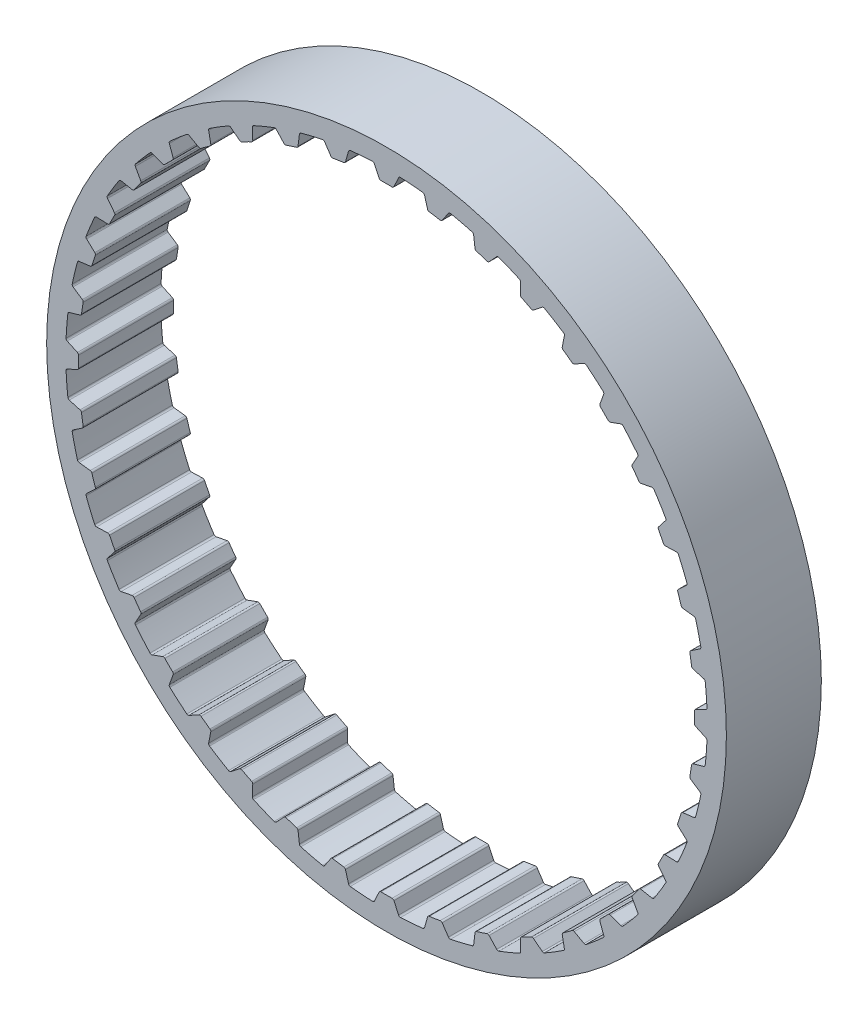
SolidWorks part; units mm, degrees
ref_plane "正面" through (0, 0, 0) normal (0, 0, 1) x (1, 0, 0)
ref_plane "平面" through (0, 0, 0) normal (0, 1, 0) x (1, 0, 0)
ref_plane "右側面" through (0, 0, 0) normal (1, 0, 0) x (0, 0, -1)
sketch "ｽｹｯﾁ1" plane through (0, 0, 0) normal (0, 0, 1) x (1, 0, 0)
  line L80 (31.3561, -6.1941) -> (30.4289, -5.5687)
  line L81 (30.6605, -4.1069) -> (31.7355, -3.7986)
  line L82 (31.939, -1.2127) -> (30.9254, -0.7401)
  line L83 (30.9254, 0.7401) -> (31.939, 1.2127)
  line L84 (31.7355, 3.7986) -> (30.6605, 4.1069)
  line L85 (30.4289, 5.5687) -> (31.3561, 6.1941)
  line L86 (30.7506, 8.7164) -> (29.6405, 8.8527)
  line L87 (29.1832, 10.2603) -> (30.0011, 11.0231)
  line L88 (29.0084, 13.4195) -> (27.8907, 13.3805)
  line L89 (27.2188, 14.6992) -> (27.9073, 15.5805)
  line L90 (26.552, 17.7922) -> (25.4542, 17.5788)
  line L91 (24.5842, 18.7762) -> (25.1264, 19.7544)
  line L92 (23.4418, 21.7268) -> (22.3909, 21.3443)
  line L93 (21.3443, 22.3909) -> (21.7268, 23.4418)
  line L94 (19.7544, 25.1264) -> (18.7762, 24.5842)
  line L95 (17.5788, 25.4542) -> (17.7922, 26.552)
  line L96 (15.5805, 27.9073) -> (14.6992, 27.2188)
  line L97 (13.3805, 27.8907) -> (13.4195, 29.0084)
  line L98 (11.0231, 30.0011) -> (10.2603, 29.1832)
  line L99 (8.8527, 29.6405) -> (8.7164, 30.7506)
  line L100 (6.1941, 31.3561) -> (5.5687, 30.4289)
  line L101 (4.1069, 30.6605) -> (3.7986, 31.7355)
  line L102 (1.2127, 31.939) -> (0.7401, 30.9254)
  line L103 (-0.7401, 30.9254) -> (-1.2127, 31.939)
  line L104 (-3.7986, 31.7355) -> (-4.1069, 30.6605)
  line L105 (-5.5687, 30.4289) -> (-6.1941, 31.3561)
  line L106 (-8.7164, 30.7506) -> (-8.8527, 29.6405)
  line L107 (-10.2603, 29.1832) -> (-11.0231, 30.0011)
  line L108 (-13.4195, 29.0084) -> (-13.3805, 27.8907)
  line L109 (-14.6992, 27.2188) -> (-15.5805, 27.9073)
  line L110 (-17.7922, 26.552) -> (-17.5788, 25.4542)
  line L111 (-18.7762, 24.5842) -> (-19.7544, 25.1264)
  line L112 (-21.7268, 23.4418) -> (-21.3443, 22.3909)
  line L113 (-22.3909, 21.3443) -> (-23.4418, 21.7268)
  line L114 (-25.1264, 19.7544) -> (-24.5842, 18.7762)
  line L115 (-25.4542, 17.5788) -> (-26.552, 17.7922)
  line L116 (-27.9073, 15.5805) -> (-27.2188, 14.6992)
  line L117 (-27.8907, 13.3805) -> (-29.0084, 13.4195)
  line L118 (-30.0011, 11.0231) -> (-29.1832, 10.2603)
  line L119 (-29.6405, 8.8527) -> (-30.7506, 8.7164)
  line L120 (-31.3561, 6.1941) -> (-30.4289, 5.5687)
  line L121 (-30.6605, 4.1069) -> (-31.7355, 3.7986)
  line L122 (-31.939, 1.2127) -> (-30.9254, 0.7401)
  line L123 (-30.9254, -0.7401) -> (-31.939, -1.2127)
  line L124 (-31.7355, -3.7986) -> (-30.6605, -4.1069)
  line L125 (-30.4289, -5.5687) -> (-31.3561, -6.1941)
  line L126 (-30.7506, -8.7164) -> (-29.6405, -8.8527)
  line L127 (-29.1832, -10.2603) -> (-30.0011, -11.0231)
  line L128 (-29.0084, -13.4195) -> (-27.8907, -13.3805)
  line L129 (-27.2188, -14.6992) -> (-27.9073, -15.5805)
  line L130 (-26.552, -17.7922) -> (-25.4542, -17.5788)
  line L131 (-24.5842, -18.7762) -> (-25.1264, -19.7544)
  line L132 (-23.4418, -21.7268) -> (-22.3909, -21.3443)
  line L133 (-21.3443, -22.3909) -> (-21.7268, -23.4418)
  line L134 (-19.7544, -25.1264) -> (-18.7762, -24.5842)
  line L135 (-17.5788, -25.4542) -> (-17.7922, -26.552)
  line L136 (-15.5805, -27.9073) -> (-14.6992, -27.2188)
  line L137 (-13.3805, -27.8907) -> (-13.4195, -29.0084)
  line L138 (-11.0231, -30.0011) -> (-10.2603, -29.1832)
  line L139 (-8.8527, -29.6405) -> (-8.7164, -30.7506)
  line L140 (-6.1941, -31.3561) -> (-5.5687, -30.4289)
  line L141 (-4.1069, -30.6605) -> (-3.7986, -31.7355)
  line L142 (-1.2127, -31.939) -> (-0.7401, -30.9254)
  line L143 (0.7401, -30.9254) -> (1.2127, -31.939)
  line L144 (3.7986, -31.7355) -> (4.1069, -30.6605)
  line L145 (5.5687, -30.4289) -> (6.1941, -31.3561)
  line L146 (8.7164, -30.7506) -> (8.8527, -29.6405)
  line L147 (10.2603, -29.1832) -> (11.0231, -30.0011)
  line L148 (13.4195, -29.0084) -> (13.3805, -27.8907)
  line L149 (14.6992, -27.2188) -> (15.5805, -27.9073)
  line L150 (17.7922, -26.552) -> (17.5788, -25.4542)
  line L151 (18.7762, -24.5842) -> (19.7544, -25.1264)
  line L152 (21.7268, -23.4418) -> (21.3443, -22.3909)
  line L153 (22.3909, -21.3443) -> (23.4418, -21.7268)
  line L154 (25.1264, -19.7544) -> (24.5842, -18.7762)
  line L155 (25.4542, -17.5788) -> (26.552, -17.7922)
  line L156 (27.9073, -15.5805) -> (27.2188, -14.6992)
  line L157 (27.8907, -13.3805) -> (29.0084, -13.4195)
  line L158 (30.0011, -11.0231) -> (29.1832, -10.2603)
  line L159 (29.6405, -8.8527) -> (30.7506, -8.7164)
  line L160 (31.3561, -6.1941) -> (30.4289, -5.5687)
  line L161 (30.6605, -4.1069) -> (31.7355, -3.7986)
  line L162 (31.939, -1.2127) -> (30.9254, -0.7401)
  line L163 (30.9254, 0.7401) -> (31.939, 1.2127)
  line L164 (31.7355, 3.7986) -> (30.6605, 4.1069)
  line L165 (30.4289, 5.5687) -> (31.3561, 6.1941)
  line L166 (30.7506, 8.7164) -> (29.6405, 8.8527)
  line L167 (29.1832, 10.2603) -> (30.0011, 11.0231)
  line L168 (29.0084, 13.4195) -> (27.8907, 13.3805)
  line L169 (27.2188, 14.6992) -> (27.9073, 15.5805)
  line L170 (26.552, 17.7922) -> (25.4542, 17.5788)
  line L171 (24.5842, 18.7762) -> (25.1264, 19.7544)
  line L172 (23.4418, 21.7268) -> (22.3909, 21.3443)
  line L173 (21.3443, 22.3909) -> (21.7268, 23.4418)
  line L174 (19.7544, 25.1264) -> (18.7762, 24.5842)
  line L175 (17.5788, 25.4542) -> (17.7922, 26.552)
  line L176 (15.5805, 27.9073) -> (14.6992, 27.2188)
  line L177 (13.3805, 27.8907) -> (13.4195, 29.0084)
  line L178 (11.0231, 30.0011) -> (10.2603, 29.1832)
  line L179 (8.8527, 29.6405) -> (8.7164, 30.7506)
  line L180 (6.1941, 31.3561) -> (5.5687, 30.4289)
  line L181 (4.1069, 30.6605) -> (3.7986, 31.7355)
  line L182 (1.2127, 31.939) -> (0.7401, 30.9254)
  line L183 (-0.7401, 30.9254) -> (-1.2127, 31.939)
  line L184 (-3.7986, 31.7355) -> (-4.1069, 30.6605)
  line L185 (-5.5687, 30.4289) -> (-6.1941, 31.3561)
  line L186 (-8.7164, 30.7506) -> (-8.8527, 29.6405)
  line L187 (-10.2603, 29.1832) -> (-11.0231, 30.0011)
  line L188 (-13.4195, 29.0084) -> (-13.3805, 27.8907)
  line L189 (-14.6992, 27.2188) -> (-15.5805, 27.9073)
  line L190 (-17.7922, 26.552) -> (-17.5788, 25.4542)
  line L191 (-18.7762, 24.5842) -> (-19.7544, 25.1264)
  line L192 (-21.7268, 23.4418) -> (-21.3443, 22.3909)
  line L193 (-22.3909, 21.3443) -> (-23.4418, 21.7268)
  line L194 (-25.1264, 19.7544) -> (-24.5842, 18.7762)
  line L195 (-25.4542, 17.5788) -> (-26.552, 17.7922)
  line L196 (-27.9073, 15.5805) -> (-27.2188, 14.6992)
  line L197 (-27.8907, 13.3805) -> (-29.0084, 13.4195)
  line L198 (-30.0011, 11.0231) -> (-29.1832, 10.2603)
  line L199 (-29.6405, 8.8527) -> (-30.7506, 8.7164)
  line L200 (-31.3561, 6.1941) -> (-30.4289, 5.5687)
  line L201 (-30.6605, 4.1069) -> (-31.7355, 3.7986)
  line L202 (-31.939, 1.2127) -> (-30.9254, 0.7401)
  line L203 (-30.9254, -0.7401) -> (-31.939, -1.2127)
  line L204 (-31.7355, -3.7986) -> (-30.6605, -4.1069)
  line L205 (-30.4289, -5.5687) -> (-31.3561, -6.1941)
  line L206 (-30.7506, -8.7164) -> (-29.6405, -8.8527)
  line L207 (-29.1832, -10.2603) -> (-30.0011, -11.0231)
  line L208 (-29.0084, -13.4195) -> (-27.8907, -13.3805)
  line L209 (-27.2188, -14.6992) -> (-27.9073, -15.5805)
  line L210 (-26.552, -17.7922) -> (-25.4542, -17.5788)
  line L211 (-24.5842, -18.7762) -> (-25.1264, -19.7544)
  line L212 (-23.4418, -21.7268) -> (-22.3909, -21.3443)
  line L213 (-21.3443, -22.3909) -> (-21.7268, -23.4418)
  line L214 (-19.7544, -25.1264) -> (-18.7762, -24.5842)
  line L215 (-17.5788, -25.4542) -> (-17.7922, -26.552)
  line L216 (-15.5805, -27.9073) -> (-14.6992, -27.2188)
  line L217 (-13.3805, -27.8907) -> (-13.4195, -29.0084)
  line L218 (-11.0231, -30.0011) -> (-10.2603, -29.1832)
  line L219 (-8.8527, -29.6405) -> (-8.7164, -30.7506)
  line L220 (-6.1941, -31.3561) -> (-5.5687, -30.4289)
  line L221 (-4.1069, -30.6605) -> (-3.7986, -31.7355)
  line L222 (-1.2127, -31.939) -> (-0.7401, -30.9254)
  line L223 (0.7401, -30.9254) -> (1.2127, -31.939)
  line L224 (3.7986, -31.7355) -> (4.1069, -30.6605)
  line L225 (5.5687, -30.4289) -> (6.1941, -31.3561)
  line L226 (8.7164, -30.7506) -> (8.8527, -29.6405)
  line L227 (10.2603, -29.1832) -> (11.0231, -30.0011)
  line L228 (13.4195, -29.0084) -> (13.3805, -27.8907)
  line L229 (14.6992, -27.2188) -> (15.5805, -27.9073)
  line L230 (17.7922, -26.552) -> (17.5788, -25.4542)
  line L231 (18.7762, -24.5842) -> (19.7544, -25.1264)
  line L232 (21.7268, -23.4418) -> (21.3443, -22.3909)
  line L233 (22.3909, -21.3443) -> (23.4418, -21.7268)
  line L234 (25.1264, -19.7544) -> (24.5842, -18.7762)
  line L235 (25.4542, -17.5788) -> (26.552, -17.7922)
  line L236 (27.9073, -15.5805) -> (27.2188, -14.6992)
  line L237 (27.8907, -13.3805) -> (29.0084, -13.4195)
  line L238 (30.0011, -11.0231) -> (29.1832, -10.2603)
  line L239 (29.6405, -8.8527) -> (30.7506, -8.7164)
  circle A0 centre (0, 0) radius 34
  arc A240 (30.7506, -8.7164) -> (30.9189, -8.5713) centre (30.7262, -8.5179) ccw
  arc A241 (30.9189, -8.5713) -> (31.4403, -6.3998) centre (0, 0) ccw
  arc A242 (31.4403, -6.3998) -> (31.3561, -6.1941) centre (31.2443, -6.3599) ccw
  arc A243 (30.3438, -5.3681) -> (30.4289, -5.5687) centre (30.5408, -5.4029) ccw
  arc A244 (30.3438, -5.3681) -> (30.5175, -4.2714) centre (0, 0) ccw
  arc A245 (30.6605, -4.1069) -> (30.5175, -4.2714) centre (30.7156, -4.2991) ccw
  arc A246 (31.7355, -3.7986) -> (31.8791, -3.629) centre (31.6804, -3.6063) ccw
  arc A247 (31.8791, -3.629) -> (32.0543, -1.4027) centre (0, 0) ccw
  arc A248 (32.0543, -1.4027) -> (31.939, -1.2127) centre (31.8545, -1.394) ccw
  arc A249 (30.81, -0.5552) -> (30.9254, -0.7401) centre (31.01, -0.5588) ccw
  arc A250 (30.81, -0.5552) -> (30.81, 0.5552) centre (0, 0) ccw
  arc A251 (30.9254, 0.7401) -> (30.81, 0.5552) centre (31.01, 0.5588) ccw
  arc A252 (31.939, 1.2127) -> (32.0543, 1.4027) centre (31.8545, 1.394) ccw
  arc A253 (32.0543, 1.4027) -> (31.8791, 3.629) centre (0, 0) ccw
  arc A254 (31.8791, 3.629) -> (31.7355, 3.7986) centre (31.6804, 3.6063) ccw
  arc A255 (30.5175, 4.2714) -> (30.6605, 4.1069) centre (30.7156, 4.2991) ccw
  arc A256 (30.5175, 4.2714) -> (30.3438, 5.3681) centre (0, 0) ccw
  arc A257 (30.4289, 5.5687) -> (30.3438, 5.3681) centre (30.5408, 5.4029) ccw
  arc A258 (31.3561, 6.1941) -> (31.4403, 6.3998) centre (31.2443, 6.3599) ccw
  arc A259 (31.4403, 6.3998) -> (30.9189, 8.5713) centre (0, 0) ccw
  arc A260 (30.9189, 8.5713) -> (30.7506, 8.7164) centre (30.7262, 8.5179) ccw
  arc A261 (29.4736, 8.9928) -> (29.6405, 8.8527) centre (29.6649, 9.0512) ccw
  arc A262 (29.4736, 8.9928) -> (29.1305, 10.0488) centre (0, 0) ccw
  arc A263 (29.1832, 10.2603) -> (29.1305, 10.0488) centre (29.3196, 10.114) ccw
  arc A264 (30.0011, 11.0231) -> (30.052, 11.2394) centre (29.8647, 11.1693) ccw
  arc A265 (30.052, 11.2394) -> (29.1974, 13.3025) centre (0, 0) ccw
  arc A266 (29.1974, 13.3025) -> (29.0084, 13.4195) centre (29.0154, 13.2196) ccw
  arc A267 (27.704, 13.4928) -> (27.8907, 13.3805) centre (27.8838, 13.5803) ccw
  arc A268 (27.704, 13.4928) -> (27.1999, 14.4821) centre (0, 0) ccw
  arc A269 (27.2188, 14.6992) -> (27.1999, 14.4821) centre (27.3764, 14.5761) ccw
  arc A270 (27.9073, 15.5805) -> (27.9238, 15.8022) centre (27.7497, 15.7037) ccw
  arc A271 (27.9238, 15.8022) -> (26.757, 17.7062) centre (0, 0) ccw
  arc A272 (26.757, 17.7062) -> (26.552, 17.7922) centre (26.5902, 17.5959) ccw
  arc A273 (25.2521, 17.6605) -> (25.4542, 17.5788) centre (25.416, 17.7751) ccw
  arc A274 (25.2521, 17.6605) -> (24.5995, 18.5588) centre (0, 0) ccw
  arc A275 (24.5842, 18.7762) -> (24.5995, 18.5588) centre (24.7591, 18.6793) ccw
  arc A276 (25.1264, 19.7544) -> (25.108, 19.9759) centre (24.9515, 19.8514) ccw
  arc A277 (25.108, 19.9759) -> (23.6577, 21.674) centre (0, 0) ccw
  arc A278 (23.6577, 21.674) -> (23.4418, 21.7268) centre (23.5102, 21.5389) ccw
  arc A279 (22.1785, 21.3934) -> (22.3909, 21.3443) centre (22.3225, 21.5322) ccw
  arc A280 (22.1785, 21.3934) -> (21.3934, 22.1785) centre (0, 0) ccw
  arc A281 (21.3443, 22.3909) -> (21.3934, 22.1785) centre (21.5322, 22.3225) ccw
  arc A282 (21.7268, 23.4418) -> (21.674, 23.6577) centre (21.5389, 23.5102) ccw
  arc A283 (21.674, 23.6577) -> (19.9759, 25.108) centre (0, 0) ccw
  arc A284 (19.9759, 25.108) -> (19.7544, 25.1264) centre (19.8514, 24.9515) ccw
  arc A285 (18.5588, 24.5995) -> (18.7762, 24.5842) centre (18.6793, 24.7591) ccw
  arc A286 (18.5588, 24.5995) -> (17.6605, 25.2521) centre (0, 0) ccw
  arc A287 (17.5788, 25.4542) -> (17.6605, 25.2521) centre (17.7751, 25.416) ccw
  arc A288 (17.7922, 26.552) -> (17.7062, 26.757) centre (17.5959, 26.5902) ccw
  arc A289 (17.7062, 26.757) -> (15.8022, 27.9238) centre (0, 0) ccw
  arc A290 (15.8022, 27.9238) -> (15.5805, 27.9073) centre (15.7037, 27.7497) ccw
  arc A291 (14.4821, 27.1999) -> (14.6992, 27.2188) centre (14.5761, 27.3764) ccw
  arc A292 (14.4821, 27.1999) -> (13.4928, 27.704) centre (0, 0) ccw
  arc A293 (13.3805, 27.8907) -> (13.4928, 27.704) centre (13.5803, 27.8838) ccw
  arc A294 (13.4195, 29.0084) -> (13.3025, 29.1974) centre (13.2196, 29.0154) ccw
  arc A295 (13.3025, 29.1974) -> (11.2394, 30.052) centre (0, 0) ccw
  arc A296 (11.2394, 30.052) -> (11.0231, 30.0011) centre (11.1693, 29.8647) ccw
  arc A297 (10.0488, 29.1305) -> (10.2603, 29.1832) centre (10.114, 29.3196) ccw
  arc A298 (10.0488, 29.1305) -> (8.9928, 29.4736) centre (0, 0) ccw
  arc A299 (8.8527, 29.6405) -> (8.9928, 29.4736) centre (9.0512, 29.6649) ccw
  arc A300 (8.7164, 30.7506) -> (8.5713, 30.9189) centre (8.5179, 30.7262) ccw
  arc A301 (8.5713, 30.9189) -> (6.3998, 31.4403) centre (0, 0) ccw
  arc A302 (6.3998, 31.4403) -> (6.1941, 31.3561) centre (6.3599, 31.2443) ccw
  arc A303 (5.3681, 30.3438) -> (5.5687, 30.4289) centre (5.4029, 30.5408) ccw
  arc A304 (5.3681, 30.3438) -> (4.2714, 30.5175) centre (0, 0) ccw
  arc A305 (4.1069, 30.6605) -> (4.2714, 30.5175) centre (4.2991, 30.7156) ccw
  arc A306 (3.7986, 31.7355) -> (3.629, 31.8791) centre (3.6063, 31.6804) ccw
  arc A307 (3.629, 31.8791) -> (1.4027, 32.0543) centre (0, 0) ccw
  arc A308 (1.4027, 32.0543) -> (1.2127, 31.939) centre (1.394, 31.8545) ccw
  arc A309 (0.5552, 30.81) -> (0.7401, 30.9254) centre (0.5588, 31.01) ccw
  arc A310 (0.5552, 30.81) -> (-0.5552, 30.81) centre (0, 0) ccw
  arc A311 (-0.7401, 30.9254) -> (-0.5552, 30.81) centre (-0.5588, 31.01) ccw
  arc A312 (-1.2127, 31.939) -> (-1.4027, 32.0543) centre (-1.394, 31.8545) ccw
  arc A313 (-1.4027, 32.0543) -> (-3.629, 31.8791) centre (0, 0) ccw
  arc A314 (-3.629, 31.8791) -> (-3.7986, 31.7355) centre (-3.6063, 31.6804) ccw
  arc A315 (-4.2714, 30.5175) -> (-4.1069, 30.6605) centre (-4.2991, 30.7156) ccw
  arc A316 (-4.2714, 30.5175) -> (-5.3681, 30.3438) centre (0, 0) ccw
  arc A317 (-5.5687, 30.4289) -> (-5.3681, 30.3438) centre (-5.4029, 30.5408) ccw
  arc A318 (-6.1941, 31.3561) -> (-6.3998, 31.4403) centre (-6.3599, 31.2443) ccw
  arc A319 (-6.3998, 31.4403) -> (-8.5713, 30.9189) centre (0, 0) ccw
  arc A320 (-8.5713, 30.9189) -> (-8.7164, 30.7506) centre (-8.5179, 30.7262) ccw
  arc A321 (-8.9928, 29.4736) -> (-8.8527, 29.6405) centre (-9.0512, 29.6649) ccw
  arc A322 (-8.9928, 29.4736) -> (-10.0488, 29.1305) centre (0, 0) ccw
  arc A323 (-10.2603, 29.1832) -> (-10.0488, 29.1305) centre (-10.114, 29.3196) ccw
  arc A324 (-11.0231, 30.0011) -> (-11.2394, 30.052) centre (-11.1693, 29.8647) ccw
  arc A325 (-11.2394, 30.052) -> (-13.3025, 29.1974) centre (0, 0) ccw
  arc A326 (-13.3025, 29.1974) -> (-13.4195, 29.0084) centre (-13.2196, 29.0154) ccw
  arc A327 (-13.4928, 27.704) -> (-13.3805, 27.8907) centre (-13.5803, 27.8838) ccw
  arc A328 (-13.4928, 27.704) -> (-14.4821, 27.1999) centre (0, 0) ccw
  arc A329 (-14.6992, 27.2188) -> (-14.4821, 27.1999) centre (-14.5761, 27.3764) ccw
  arc A330 (-15.5805, 27.9073) -> (-15.8022, 27.9238) centre (-15.7037, 27.7497) ccw
  arc A331 (-15.8022, 27.9238) -> (-17.7062, 26.757) centre (0, 0) ccw
  arc A332 (-17.7062, 26.757) -> (-17.7922, 26.552) centre (-17.5959, 26.5902) ccw
  arc A333 (-17.6605, 25.2521) -> (-17.5788, 25.4542) centre (-17.7751, 25.416) ccw
  arc A334 (-17.6605, 25.2521) -> (-18.5588, 24.5995) centre (0, 0) ccw
  arc A335 (-18.7762, 24.5842) -> (-18.5588, 24.5995) centre (-18.6793, 24.7591) ccw
  arc A336 (-19.7544, 25.1264) -> (-19.9759, 25.108) centre (-19.8514, 24.9515) ccw
  arc A337 (-19.9759, 25.108) -> (-21.674, 23.6577) centre (0, 0) ccw
  arc A338 (-21.674, 23.6577) -> (-21.7268, 23.4418) centre (-21.5389, 23.5102) ccw
  arc A339 (-21.3934, 22.1785) -> (-21.3443, 22.3909) centre (-21.5322, 22.3225) ccw
  arc A340 (-21.3934, 22.1785) -> (-22.1785, 21.3934) centre (0, 0) ccw
  arc A341 (-22.3909, 21.3443) -> (-22.1785, 21.3934) centre (-22.3225, 21.5322) ccw
  arc A342 (-23.4418, 21.7268) -> (-23.6577, 21.674) centre (-23.5102, 21.5389) ccw
  arc A343 (-23.6577, 21.674) -> (-25.108, 19.9759) centre (0, 0) ccw
  arc A344 (-25.108, 19.9759) -> (-25.1264, 19.7544) centre (-24.9515, 19.8514) ccw
  arc A345 (-24.5995, 18.5588) -> (-24.5842, 18.7762) centre (-24.7591, 18.6793) ccw
  arc A346 (-24.5995, 18.5588) -> (-25.2521, 17.6605) centre (0, 0) ccw
  arc A347 (-25.4542, 17.5788) -> (-25.2521, 17.6605) centre (-25.416, 17.7751) ccw
  arc A348 (-26.552, 17.7922) -> (-26.757, 17.7062) centre (-26.5902, 17.5959) ccw
  arc A349 (-26.757, 17.7062) -> (-27.9238, 15.8022) centre (0, 0) ccw
  arc A350 (-27.9238, 15.8022) -> (-27.9073, 15.5805) centre (-27.7497, 15.7037) ccw
  arc A351 (-27.1999, 14.4821) -> (-27.2188, 14.6992) centre (-27.3764, 14.5761) ccw
  arc A352 (-27.1999, 14.4821) -> (-27.704, 13.4928) centre (0, 0) ccw
  arc A353 (-27.8907, 13.3805) -> (-27.704, 13.4928) centre (-27.8838, 13.5803) ccw
  arc A354 (-29.0084, 13.4195) -> (-29.1974, 13.3025) centre (-29.0154, 13.2196) ccw
  arc A355 (-29.1974, 13.3025) -> (-30.052, 11.2394) centre (0, 0) ccw
  arc A356 (-30.052, 11.2394) -> (-30.0011, 11.0231) centre (-29.8647, 11.1693) ccw
  arc A357 (-29.1305, 10.0488) -> (-29.1832, 10.2603) centre (-29.3196, 10.114) ccw
  arc A358 (-29.1305, 10.0488) -> (-29.4736, 8.9928) centre (0, 0) ccw
  arc A359 (-29.6405, 8.8527) -> (-29.4736, 8.9928) centre (-29.6649, 9.0512) ccw
  arc A360 (-30.7506, 8.7164) -> (-30.9189, 8.5713) centre (-30.7262, 8.5179) ccw
  arc A361 (-30.9189, 8.5713) -> (-31.4403, 6.3998) centre (0, 0) ccw
  arc A362 (-31.4403, 6.3998) -> (-31.3561, 6.1941) centre (-31.2443, 6.3599) ccw
  arc A363 (-30.3438, 5.3681) -> (-30.4289, 5.5687) centre (-30.5408, 5.4029) ccw
  arc A364 (-30.3438, 5.3681) -> (-30.5175, 4.2714) centre (0, 0) ccw
  arc A365 (-30.6605, 4.1069) -> (-30.5175, 4.2714) centre (-30.7156, 4.2991) ccw
  arc A366 (-31.7355, 3.7986) -> (-31.8791, 3.629) centre (-31.6804, 3.6063) ccw
  arc A367 (-31.8791, 3.629) -> (-32.0543, 1.4027) centre (0, 0) ccw
  arc A368 (-32.0543, 1.4027) -> (-31.939, 1.2127) centre (-31.8545, 1.394) ccw
  arc A369 (-30.81, 0.5552) -> (-30.9254, 0.7401) centre (-31.01, 0.5588) ccw
  arc A370 (-30.81, 0.5552) -> (-30.81, -0.5552) centre (0, 0) ccw
  arc A371 (-30.9254, -0.7401) -> (-30.81, -0.5552) centre (-31.01, -0.5588) ccw
  arc A372 (-31.939, -1.2127) -> (-32.0543, -1.4027) centre (-31.8545, -1.394) ccw
  arc A373 (-32.0543, -1.4027) -> (-31.8791, -3.629) centre (0, 0) ccw
  arc A374 (-31.8791, -3.629) -> (-31.7355, -3.7986) centre (-31.6804, -3.6063) ccw
  arc A375 (-30.5175, -4.2714) -> (-30.6605, -4.1069) centre (-30.7156, -4.2991) ccw
  arc A376 (-30.5175, -4.2714) -> (-30.3438, -5.3681) centre (0, 0) ccw
  arc A377 (-30.4289, -5.5687) -> (-30.3438, -5.3681) centre (-30.5408, -5.4029) ccw
  arc A378 (-31.3561, -6.1941) -> (-31.4403, -6.3998) centre (-31.2443, -6.3599) ccw
  arc A379 (-31.4403, -6.3998) -> (-30.9189, -8.5713) centre (0, 0) ccw
  arc A380 (-30.9189, -8.5713) -> (-30.7506, -8.7164) centre (-30.7262, -8.5179) ccw
  arc A381 (-29.4736, -8.9928) -> (-29.6405, -8.8527) centre (-29.6649, -9.0512) ccw
  arc A382 (-29.4736, -8.9928) -> (-29.1305, -10.0488) centre (0, 0) ccw
  arc A383 (-29.1832, -10.2603) -> (-29.1305, -10.0488) centre (-29.3196, -10.114) ccw
  arc A384 (-30.0011, -11.0231) -> (-30.052, -11.2394) centre (-29.8647, -11.1693) ccw
  arc A385 (-30.052, -11.2394) -> (-29.1974, -13.3025) centre (0, 0) ccw
  arc A386 (-29.1974, -13.3025) -> (-29.0084, -13.4195) centre (-29.0154, -13.2196) ccw
  arc A387 (-27.704, -13.4928) -> (-27.8907, -13.3805) centre (-27.8838, -13.5803) ccw
  arc A388 (-27.704, -13.4928) -> (-27.1999, -14.4821) centre (0, 0) ccw
  arc A389 (-27.2188, -14.6992) -> (-27.1999, -14.4821) centre (-27.3764, -14.5761) ccw
  arc A390 (-27.9073, -15.5805) -> (-27.9238, -15.8022) centre (-27.7497, -15.7037) ccw
  arc A391 (-27.9238, -15.8022) -> (-26.757, -17.7062) centre (0, 0) ccw
  arc A392 (-26.757, -17.7062) -> (-26.552, -17.7922) centre (-26.5902, -17.5959) ccw
  arc A393 (-25.2521, -17.6605) -> (-25.4542, -17.5788) centre (-25.416, -17.7751) ccw
  arc A394 (-25.2521, -17.6605) -> (-24.5995, -18.5588) centre (0, 0) ccw
  arc A395 (-24.5842, -18.7762) -> (-24.5995, -18.5588) centre (-24.7591, -18.6793) ccw
  arc A396 (-25.1264, -19.7544) -> (-25.108, -19.9759) centre (-24.9515, -19.8514) ccw
  arc A397 (-25.108, -19.9759) -> (-23.6577, -21.674) centre (0, 0) ccw
  arc A398 (-23.6577, -21.674) -> (-23.4418, -21.7268) centre (-23.5102, -21.5389) ccw
  arc A399 (-22.1785, -21.3934) -> (-22.3909, -21.3443) centre (-22.3225, -21.5322) ccw
  arc A400 (-22.1785, -21.3934) -> (-21.3934, -22.1785) centre (0, 0) ccw
  arc A401 (-21.3443, -22.3909) -> (-21.3934, -22.1785) centre (-21.5322, -22.3225) ccw
  arc A402 (-21.7268, -23.4418) -> (-21.674, -23.6577) centre (-21.5389, -23.5102) ccw
  arc A403 (-21.674, -23.6577) -> (-19.9759, -25.108) centre (0, 0) ccw
  arc A404 (-19.9759, -25.108) -> (-19.7544, -25.1264) centre (-19.8514, -24.9515) ccw
  arc A405 (-18.5588, -24.5995) -> (-18.7762, -24.5842) centre (-18.6793, -24.7591) ccw
  arc A406 (-18.5588, -24.5995) -> (-17.6605, -25.2521) centre (0, 0) ccw
  arc A407 (-17.5788, -25.4542) -> (-17.6605, -25.2521) centre (-17.7751, -25.416) ccw
  arc A408 (-17.7922, -26.552) -> (-17.7062, -26.757) centre (-17.5959, -26.5902) ccw
  arc A409 (-17.7062, -26.757) -> (-15.8022, -27.9238) centre (0, 0) ccw
  arc A410 (-15.8022, -27.9238) -> (-15.5805, -27.9073) centre (-15.7037, -27.7497) ccw
  arc A411 (-14.4821, -27.1999) -> (-14.6992, -27.2188) centre (-14.5761, -27.3764) ccw
  arc A412 (-14.4821, -27.1999) -> (-13.4928, -27.704) centre (0, 0) ccw
  arc A413 (-13.3805, -27.8907) -> (-13.4928, -27.704) centre (-13.5803, -27.8838) ccw
  arc A414 (-13.4195, -29.0084) -> (-13.3025, -29.1974) centre (-13.2196, -29.0154) ccw
  arc A415 (-13.3025, -29.1974) -> (-11.2394, -30.052) centre (0, 0) ccw
  arc A416 (-11.2394, -30.052) -> (-11.0231, -30.0011) centre (-11.1693, -29.8647) ccw
  arc A417 (-10.0488, -29.1305) -> (-10.2603, -29.1832) centre (-10.114, -29.3196) ccw
  arc A418 (-10.0488, -29.1305) -> (-8.9928, -29.4736) centre (0, 0) ccw
  arc A419 (-8.8527, -29.6405) -> (-8.9928, -29.4736) centre (-9.0512, -29.6649) ccw
  arc A420 (-8.7164, -30.7506) -> (-8.5713, -30.9189) centre (-8.5179, -30.7262) ccw
  arc A421 (-8.5713, -30.9189) -> (-6.3998, -31.4403) centre (0, 0) ccw
  arc A422 (-6.3998, -31.4403) -> (-6.1941, -31.3561) centre (-6.3599, -31.2443) ccw
  arc A423 (-5.3681, -30.3438) -> (-5.5687, -30.4289) centre (-5.4029, -30.5408) ccw
  arc A424 (-5.3681, -30.3438) -> (-4.2714, -30.5175) centre (0, 0) ccw
  arc A425 (-4.1069, -30.6605) -> (-4.2714, -30.5175) centre (-4.2991, -30.7156) ccw
  arc A426 (-3.7986, -31.7355) -> (-3.629, -31.8791) centre (-3.6063, -31.6804) ccw
  arc A427 (-3.629, -31.8791) -> (-1.4027, -32.0543) centre (0, 0) ccw
  arc A428 (-1.4027, -32.0543) -> (-1.2127, -31.939) centre (-1.394, -31.8545) ccw
  arc A429 (-0.5552, -30.81) -> (-0.7401, -30.9254) centre (-0.5588, -31.01) ccw
  arc A430 (-0.5552, -30.81) -> (0.5552, -30.81) centre (0, 0) ccw
  arc A431 (0.7401, -30.9254) -> (0.5552, -30.81) centre (0.5588, -31.01) ccw
  arc A432 (1.2127, -31.939) -> (1.4027, -32.0543) centre (1.394, -31.8545) ccw
  arc A433 (1.4027, -32.0543) -> (3.629, -31.8791) centre (0, 0) ccw
  arc A434 (3.629, -31.8791) -> (3.7986, -31.7355) centre (3.6063, -31.6804) ccw
  arc A435 (4.2714, -30.5175) -> (4.1069, -30.6605) centre (4.2991, -30.7156) ccw
  arc A436 (4.2714, -30.5175) -> (5.3681, -30.3438) centre (0, 0) ccw
  arc A437 (5.5687, -30.4289) -> (5.3681, -30.3438) centre (5.4029, -30.5408) ccw
  arc A438 (6.1941, -31.3561) -> (6.3998, -31.4403) centre (6.3599, -31.2443) ccw
  arc A439 (6.3998, -31.4403) -> (8.5713, -30.9189) centre (0, 0) ccw
  arc A440 (8.5713, -30.9189) -> (8.7164, -30.7506) centre (8.5179, -30.7262) ccw
  arc A441 (8.9928, -29.4736) -> (8.8527, -29.6405) centre (9.0512, -29.6649) ccw
  arc A442 (8.9928, -29.4736) -> (10.0488, -29.1305) centre (0, 0) ccw
  arc A443 (10.2603, -29.1832) -> (10.0488, -29.1305) centre (10.114, -29.3196) ccw
  arc A444 (11.0231, -30.0011) -> (11.2394, -30.052) centre (11.1693, -29.8647) ccw
  arc A445 (11.2394, -30.052) -> (13.3025, -29.1974) centre (0, 0) ccw
  arc A446 (13.3025, -29.1974) -> (13.4195, -29.0084) centre (13.2196, -29.0154) ccw
  arc A447 (13.4928, -27.704) -> (13.3805, -27.8907) centre (13.5803, -27.8838) ccw
  arc A448 (13.4928, -27.704) -> (14.4821, -27.1999) centre (0, 0) ccw
  arc A449 (14.6992, -27.2188) -> (14.4821, -27.1999) centre (14.5761, -27.3764) ccw
  arc A450 (15.5805, -27.9073) -> (15.8022, -27.9238) centre (15.7037, -27.7497) ccw
  arc A451 (15.8022, -27.9238) -> (17.7062, -26.757) centre (0, 0) ccw
  arc A452 (17.7062, -26.757) -> (17.7922, -26.552) centre (17.5959, -26.5902) ccw
  arc A453 (17.6605, -25.2521) -> (17.5788, -25.4542) centre (17.7751, -25.416) ccw
  arc A454 (17.6605, -25.2521) -> (18.5588, -24.5995) centre (0, 0) ccw
  arc A455 (18.7762, -24.5842) -> (18.5588, -24.5995) centre (18.6793, -24.7591) ccw
  arc A456 (19.7544, -25.1264) -> (19.9759, -25.108) centre (19.8514, -24.9515) ccw
  arc A457 (19.9759, -25.108) -> (21.674, -23.6577) centre (0, 0) ccw
  arc A458 (21.674, -23.6577) -> (21.7268, -23.4418) centre (21.5389, -23.5102) ccw
  arc A459 (21.3934, -22.1785) -> (21.3443, -22.3909) centre (21.5322, -22.3225) ccw
  arc A460 (21.3934, -22.1785) -> (22.1785, -21.3934) centre (0, 0) ccw
  arc A461 (22.3909, -21.3443) -> (22.1785, -21.3934) centre (22.3225, -21.5322) ccw
  arc A462 (23.4418, -21.7268) -> (23.6577, -21.674) centre (23.5102, -21.5389) ccw
  arc A463 (23.6577, -21.674) -> (25.108, -19.9759) centre (0, 0) ccw
  arc A464 (25.108, -19.9759) -> (25.1264, -19.7544) centre (24.9515, -19.8514) ccw
  arc A465 (24.5995, -18.5588) -> (24.5842, -18.7762) centre (24.7591, -18.6793) ccw
  arc A466 (24.5995, -18.5588) -> (25.2521, -17.6605) centre (0, 0) ccw
  arc A467 (25.4542, -17.5788) -> (25.2521, -17.6605) centre (25.416, -17.7751) ccw
  arc A468 (26.552, -17.7922) -> (26.757, -17.7062) centre (26.5902, -17.5959) ccw
  arc A469 (26.757, -17.7062) -> (27.9238, -15.8022) centre (0, 0) ccw
  arc A470 (27.9238, -15.8022) -> (27.9073, -15.5805) centre (27.7497, -15.7037) ccw
  arc A471 (27.1999, -14.4821) -> (27.2188, -14.6992) centre (27.3764, -14.5761) ccw
  arc A472 (27.1999, -14.4821) -> (27.704, -13.4928) centre (0, 0) ccw
  arc A473 (27.8907, -13.3805) -> (27.704, -13.4928) centre (27.8838, -13.5803) ccw
  arc A474 (29.0084, -13.4195) -> (29.1974, -13.3025) centre (29.0154, -13.2196) ccw
  arc A475 (29.1974, -13.3025) -> (30.052, -11.2394) centre (0, 0) ccw
  arc A476 (30.052, -11.2394) -> (30.0011, -11.0231) centre (29.8647, -11.1693) ccw
  arc A477 (29.1305, -10.0488) -> (29.1832, -10.2603) centre (29.3196, -10.114) ccw
  arc A478 (29.1305, -10.0488) -> (29.4736, -8.9928) centre (0, 0) ccw
  arc A479 (29.6405, -8.8527) -> (29.4736, -8.9928) centre (29.6649, -9.0512) ccw
  arc A480 (30.7506, -8.7164) -> (30.9189, -8.5713) centre (30.7262, -8.5179) ccw
  arc A481 (30.9189, -8.5713) -> (31.4403, -6.3998) centre (0, 0) ccw
  arc A482 (31.4403, -6.3998) -> (31.3561, -6.1941) centre (31.2443, -6.3599) ccw
  arc A483 (30.3438, -5.3681) -> (30.4289, -5.5687) centre (30.5408, -5.4029) ccw
  arc A484 (30.3438, -5.3681) -> (30.5175, -4.2714) centre (0, 0) ccw
  arc A485 (30.6605, -4.1069) -> (30.5175, -4.2714) centre (30.7156, -4.2991) ccw
  arc A486 (31.7355, -3.7986) -> (31.8791, -3.629) centre (31.6804, -3.6063) ccw
  arc A487 (31.8791, -3.629) -> (32.0543, -1.4027) centre (0, 0) ccw
  arc A488 (32.0543, -1.4027) -> (31.939, -1.2127) centre (31.8545, -1.394) ccw
  arc A489 (30.81, -0.5552) -> (30.9254, -0.7401) centre (31.01, -0.5588) ccw
  arc A490 (30.81, -0.5552) -> (30.81, 0.5552) centre (0, 0) ccw
  arc A491 (30.9254, 0.7401) -> (30.81, 0.5552) centre (31.01, 0.5588) ccw
  arc A492 (31.939, 1.2127) -> (32.0543, 1.4027) centre (31.8545, 1.394) ccw
  arc A493 (32.0543, 1.4027) -> (31.8791, 3.629) centre (0, 0) ccw
  arc A494 (31.8791, 3.629) -> (31.7355, 3.7986) centre (31.6804, 3.6063) ccw
  arc A495 (30.5175, 4.2714) -> (30.6605, 4.1069) centre (30.7156, 4.2991) ccw
  arc A496 (30.5175, 4.2714) -> (30.3438, 5.3681) centre (0, 0) ccw
  arc A497 (30.4289, 5.5687) -> (30.3438, 5.3681) centre (30.5408, 5.4029) ccw
  arc A498 (31.3561, 6.1941) -> (31.4403, 6.3998) centre (31.2443, 6.3599) ccw
  arc A499 (31.4403, 6.3998) -> (30.9189, 8.5713) centre (0, 0) ccw
  arc A500 (30.9189, 8.5713) -> (30.7506, 8.7164) centre (30.7262, 8.5179) ccw
  arc A501 (29.4736, 8.9928) -> (29.6405, 8.8527) centre (29.6649, 9.0512) ccw
  arc A502 (29.4736, 8.9928) -> (29.1305, 10.0488) centre (0, 0) ccw
  arc A503 (29.1832, 10.2603) -> (29.1305, 10.0488) centre (29.3196, 10.114) ccw
  arc A504 (30.0011, 11.0231) -> (30.052, 11.2394) centre (29.8647, 11.1693) ccw
  arc A505 (30.052, 11.2394) -> (29.1974, 13.3025) centre (0, 0) ccw
  arc A506 (29.1974, 13.3025) -> (29.0084, 13.4195) centre (29.0154, 13.2196) ccw
  arc A507 (27.704, 13.4928) -> (27.8907, 13.3805) centre (27.8838, 13.5803) ccw
  arc A508 (27.704, 13.4928) -> (27.1999, 14.4821) centre (0, 0) ccw
  arc A509 (27.2188, 14.6992) -> (27.1999, 14.4821) centre (27.3764, 14.5761) ccw
  arc A510 (27.9073, 15.5805) -> (27.9238, 15.8022) centre (27.7497, 15.7037) ccw
  arc A511 (27.9238, 15.8022) -> (26.757, 17.7062) centre (0, 0) ccw
  arc A512 (26.757, 17.7062) -> (26.552, 17.7922) centre (26.5902, 17.5959) ccw
  arc A513 (25.2521, 17.6605) -> (25.4542, 17.5788) centre (25.416, 17.7751) ccw
  arc A514 (25.2521, 17.6605) -> (24.5995, 18.5588) centre (0, 0) ccw
  arc A515 (24.5842, 18.7762) -> (24.5995, 18.5588) centre (24.7591, 18.6793) ccw
  arc A516 (25.1264, 19.7544) -> (25.108, 19.9759) centre (24.9515, 19.8514) ccw
  arc A517 (25.108, 19.9759) -> (23.6577, 21.674) centre (0, 0) ccw
  arc A518 (23.6577, 21.674) -> (23.4418, 21.7268) centre (23.5102, 21.5389) ccw
  arc A519 (22.1785, 21.3934) -> (22.3909, 21.3443) centre (22.3225, 21.5322) ccw
  arc A520 (22.1785, 21.3934) -> (21.3934, 22.1785) centre (0, 0) ccw
  arc A521 (21.3443, 22.3909) -> (21.3934, 22.1785) centre (21.5322, 22.3225) ccw
  arc A522 (21.7268, 23.4418) -> (21.674, 23.6577) centre (21.5389, 23.5102) ccw
  arc A523 (21.674, 23.6577) -> (19.9759, 25.108) centre (0, 0) ccw
  arc A524 (19.9759, 25.108) -> (19.7544, 25.1264) centre (19.8514, 24.9515) ccw
  arc A525 (18.5588, 24.5995) -> (18.7762, 24.5842) centre (18.6793, 24.7591) ccw
  arc A526 (18.5588, 24.5995) -> (17.6605, 25.2521) centre (0, 0) ccw
  arc A527 (17.5788, 25.4542) -> (17.6605, 25.2521) centre (17.7751, 25.416) ccw
  arc A528 (17.7922, 26.552) -> (17.7062, 26.757) centre (17.5959, 26.5902) ccw
  arc A529 (17.7062, 26.757) -> (15.8022, 27.9238) centre (0, 0) ccw
  arc A530 (15.8022, 27.9238) -> (15.5805, 27.9073) centre (15.7037, 27.7497) ccw
  arc A531 (14.4821, 27.1999) -> (14.6992, 27.2188) centre (14.5761, 27.3764) ccw
  arc A532 (14.4821, 27.1999) -> (13.4928, 27.704) centre (0, 0) ccw
  arc A533 (13.3805, 27.8907) -> (13.4928, 27.704) centre (13.5803, 27.8838) ccw
  arc A534 (13.4195, 29.0084) -> (13.3025, 29.1974) centre (13.2196, 29.0154) ccw
  arc A535 (13.3025, 29.1974) -> (11.2394, 30.052) centre (0, 0) ccw
  arc A536 (11.2394, 30.052) -> (11.0231, 30.0011) centre (11.1693, 29.8647) ccw
  arc A537 (10.0488, 29.1305) -> (10.2603, 29.1832) centre (10.114, 29.3196) ccw
  arc A538 (10.0488, 29.1305) -> (8.9928, 29.4736) centre (0, 0) ccw
  arc A539 (8.8527, 29.6405) -> (8.9928, 29.4736) centre (9.0512, 29.6649) ccw
  arc A540 (8.7164, 30.7506) -> (8.5713, 30.9189) centre (8.5179, 30.7262) ccw
  arc A541 (8.5713, 30.9189) -> (6.3998, 31.4403) centre (0, 0) ccw
  arc A542 (6.3998, 31.4403) -> (6.1941, 31.3561) centre (6.3599, 31.2443) ccw
  arc A543 (5.3681, 30.3438) -> (5.5687, 30.4289) centre (5.4029, 30.5408) ccw
  arc A544 (5.3681, 30.3438) -> (4.2714, 30.5175) centre (0, 0) ccw
  arc A545 (4.1069, 30.6605) -> (4.2714, 30.5175) centre (4.2991, 30.7156) ccw
  arc A546 (3.7986, 31.7355) -> (3.629, 31.8791) centre (3.6063, 31.6804) ccw
  arc A547 (3.629, 31.8791) -> (1.4027, 32.0543) centre (0, 0) ccw
  arc A548 (1.4027, 32.0543) -> (1.2127, 31.939) centre (1.394, 31.8545) ccw
  arc A549 (0.5552, 30.81) -> (0.7401, 30.9254) centre (0.5588, 31.01) ccw
  arc A550 (0.5552, 30.81) -> (-0.5552, 30.81) centre (0, 0) ccw
  arc A551 (-0.7401, 30.9254) -> (-0.5552, 30.81) centre (-0.5588, 31.01) ccw
  arc A552 (-1.2127, 31.939) -> (-1.4027, 32.0543) centre (-1.394, 31.8545) ccw
  arc A553 (-1.4027, 32.0543) -> (-3.629, 31.8791) centre (0, 0) ccw
  arc A554 (-3.629, 31.8791) -> (-3.7986, 31.7355) centre (-3.6063, 31.6804) ccw
  arc A555 (-4.2714, 30.5175) -> (-4.1069, 30.6605) centre (-4.2991, 30.7156) ccw
  arc A556 (-4.2714, 30.5175) -> (-5.3681, 30.3438) centre (0, 0) ccw
  arc A557 (-5.5687, 30.4289) -> (-5.3681, 30.3438) centre (-5.4029, 30.5408) ccw
  arc A558 (-6.1941, 31.3561) -> (-6.3998, 31.4403) centre (-6.3599, 31.2443) ccw
  arc A559 (-6.3998, 31.4403) -> (-8.5713, 30.9189) centre (0, 0) ccw
  arc A560 (-8.5713, 30.9189) -> (-8.7164, 30.7506) centre (-8.5179, 30.7262) ccw
  arc A561 (-8.9928, 29.4736) -> (-8.8527, 29.6405) centre (-9.0512, 29.6649) ccw
  arc A562 (-8.9928, 29.4736) -> (-10.0488, 29.1305) centre (0, 0) ccw
  arc A563 (-10.2603, 29.1832) -> (-10.0488, 29.1305) centre (-10.114, 29.3196) ccw
  arc A564 (-11.0231, 30.0011) -> (-11.2394, 30.052) centre (-11.1693, 29.8647) ccw
  arc A565 (-11.2394, 30.052) -> (-13.3025, 29.1974) centre (0, 0) ccw
  arc A566 (-13.3025, 29.1974) -> (-13.4195, 29.0084) centre (-13.2196, 29.0154) ccw
  arc A567 (-13.4928, 27.704) -> (-13.3805, 27.8907) centre (-13.5803, 27.8838) ccw
  arc A568 (-13.4928, 27.704) -> (-14.4821, 27.1999) centre (0, 0) ccw
  arc A569 (-14.6992, 27.2188) -> (-14.4821, 27.1999) centre (-14.5761, 27.3764) ccw
  arc A570 (-15.5805, 27.9073) -> (-15.8022, 27.9238) centre (-15.7037, 27.7497) ccw
  arc A571 (-15.8022, 27.9238) -> (-17.7062, 26.757) centre (0, 0) ccw
  arc A572 (-17.7062, 26.757) -> (-17.7922, 26.552) centre (-17.5959, 26.5902) ccw
  arc A573 (-17.6605, 25.2521) -> (-17.5788, 25.4542) centre (-17.7751, 25.416) ccw
  arc A574 (-17.6605, 25.2521) -> (-18.5588, 24.5995) centre (0, 0) ccw
  arc A575 (-18.7762, 24.5842) -> (-18.5588, 24.5995) centre (-18.6793, 24.7591) ccw
  arc A576 (-19.7544, 25.1264) -> (-19.9759, 25.108) centre (-19.8514, 24.9515) ccw
  arc A577 (-19.9759, 25.108) -> (-21.674, 23.6577) centre (0, 0) ccw
  arc A578 (-21.674, 23.6577) -> (-21.7268, 23.4418) centre (-21.5389, 23.5102) ccw
  arc A579 (-21.3934, 22.1785) -> (-21.3443, 22.3909) centre (-21.5322, 22.3225) ccw
  arc A580 (-21.3934, 22.1785) -> (-22.1785, 21.3934) centre (0, 0) ccw
  arc A581 (-22.3909, 21.3443) -> (-22.1785, 21.3934) centre (-22.3225, 21.5322) ccw
  arc A582 (-23.4418, 21.7268) -> (-23.6577, 21.674) centre (-23.5102, 21.5389) ccw
  arc A583 (-23.6577, 21.674) -> (-25.108, 19.9759) centre (0, 0) ccw
  arc A584 (-25.108, 19.9759) -> (-25.1264, 19.7544) centre (-24.9515, 19.8514) ccw
  arc A585 (-24.5995, 18.5588) -> (-24.5842, 18.7762) centre (-24.7591, 18.6793) ccw
  arc A586 (-24.5995, 18.5588) -> (-25.2521, 17.6605) centre (0, 0) ccw
  arc A587 (-25.4542, 17.5788) -> (-25.2521, 17.6605) centre (-25.416, 17.7751) ccw
  arc A588 (-26.552, 17.7922) -> (-26.757, 17.7062) centre (-26.5902, 17.5959) ccw
  arc A589 (-26.757, 17.7062) -> (-27.9238, 15.8022) centre (0, 0) ccw
  arc A590 (-27.9238, 15.8022) -> (-27.9073, 15.5805) centre (-27.7497, 15.7037) ccw
  arc A591 (-27.1999, 14.4821) -> (-27.2188, 14.6992) centre (-27.3764, 14.5761) ccw
  arc A592 (-27.1999, 14.4821) -> (-27.704, 13.4928) centre (0, 0) ccw
  arc A593 (-27.8907, 13.3805) -> (-27.704, 13.4928) centre (-27.8838, 13.5803) ccw
  arc A594 (-29.0084, 13.4195) -> (-29.1974, 13.3025) centre (-29.0154, 13.2196) ccw
  arc A595 (-29.1974, 13.3025) -> (-30.052, 11.2394) centre (0, 0) ccw
  arc A596 (-30.052, 11.2394) -> (-30.0011, 11.0231) centre (-29.8647, 11.1693) ccw
  arc A597 (-29.1305, 10.0488) -> (-29.1832, 10.2603) centre (-29.3196, 10.114) ccw
  arc A598 (-29.1305, 10.0488) -> (-29.4736, 8.9928) centre (0, 0) ccw
  arc A599 (-29.6405, 8.8527) -> (-29.4736, 8.9928) centre (-29.6649, 9.0512) ccw
  arc A600 (-30.7506, 8.7164) -> (-30.9189, 8.5713) centre (-30.7262, 8.5179) ccw
  arc A601 (-30.9189, 8.5713) -> (-31.4403, 6.3998) centre (0, 0) ccw
  arc A602 (-31.4403, 6.3998) -> (-31.3561, 6.1941) centre (-31.2443, 6.3599) ccw
  arc A603 (-30.3438, 5.3681) -> (-30.4289, 5.5687) centre (-30.5408, 5.4029) ccw
  arc A604 (-30.3438, 5.3681) -> (-30.5175, 4.2714) centre (0, 0) ccw
  arc A605 (-30.6605, 4.1069) -> (-30.5175, 4.2714) centre (-30.7156, 4.2991) ccw
  arc A606 (-31.7355, 3.7986) -> (-31.8791, 3.629) centre (-31.6804, 3.6063) ccw
  arc A607 (-31.8791, 3.629) -> (-32.0543, 1.4027) centre (0, 0) ccw
  arc A608 (-32.0543, 1.4027) -> (-31.939, 1.2127) centre (-31.8545, 1.394) ccw
  arc A609 (-30.81, 0.5552) -> (-30.9254, 0.7401) centre (-31.01, 0.5588) ccw
  arc A610 (-30.81, 0.5552) -> (-30.81, -0.5552) centre (0, 0) ccw
  arc A611 (-30.9254, -0.7401) -> (-30.81, -0.5552) centre (-31.01, -0.5588) ccw
  arc A612 (-31.939, -1.2127) -> (-32.0543, -1.4027) centre (-31.8545, -1.394) ccw
  arc A613 (-32.0543, -1.4027) -> (-31.8791, -3.629) centre (0, 0) ccw
  arc A614 (-31.8791, -3.629) -> (-31.7355, -3.7986) centre (-31.6804, -3.6063) ccw
  arc A615 (-30.5175, -4.2714) -> (-30.6605, -4.1069) centre (-30.7156, -4.2991) ccw
  arc A616 (-30.5175, -4.2714) -> (-30.3438, -5.3681) centre (0, 0) ccw
  arc A617 (-30.4289, -5.5687) -> (-30.3438, -5.3681) centre (-30.5408, -5.4029) ccw
  arc A618 (-31.3561, -6.1941) -> (-31.4403, -6.3998) centre (-31.2443, -6.3599) ccw
  arc A619 (-31.4403, -6.3998) -> (-30.9189, -8.5713) centre (0, 0) ccw
  arc A620 (-30.9189, -8.5713) -> (-30.7506, -8.7164) centre (-30.7262, -8.5179) ccw
  arc A621 (-29.4736, -8.9928) -> (-29.6405, -8.8527) centre (-29.6649, -9.0512) ccw
  arc A622 (-29.4736, -8.9928) -> (-29.1305, -10.0488) centre (0, 0) ccw
  arc A623 (-29.1832, -10.2603) -> (-29.1305, -10.0488) centre (-29.3196, -10.114) ccw
  arc A624 (-30.0011, -11.0231) -> (-30.052, -11.2394) centre (-29.8647, -11.1693) ccw
  arc A625 (-30.052, -11.2394) -> (-29.1974, -13.3025) centre (0, 0) ccw
  arc A626 (-29.1974, -13.3025) -> (-29.0084, -13.4195) centre (-29.0154, -13.2196) ccw
  arc A627 (-27.704, -13.4928) -> (-27.8907, -13.3805) centre (-27.8838, -13.5803) ccw
  arc A628 (-27.704, -13.4928) -> (-27.1999, -14.4821) centre (0, 0) ccw
  arc A629 (-27.2188, -14.6992) -> (-27.1999, -14.4821) centre (-27.3764, -14.5761) ccw
  arc A630 (-27.9073, -15.5805) -> (-27.9238, -15.8022) centre (-27.7497, -15.7037) ccw
  arc A631 (-27.9238, -15.8022) -> (-26.757, -17.7062) centre (0, 0) ccw
  arc A632 (-26.757, -17.7062) -> (-26.552, -17.7922) centre (-26.5902, -17.5959) ccw
  arc A633 (-25.2521, -17.6605) -> (-25.4542, -17.5788) centre (-25.416, -17.7751) ccw
  arc A634 (-25.2521, -17.6605) -> (-24.5995, -18.5588) centre (0, 0) ccw
  arc A635 (-24.5842, -18.7762) -> (-24.5995, -18.5588) centre (-24.7591, -18.6793) ccw
  arc A636 (-25.1264, -19.7544) -> (-25.108, -19.9759) centre (-24.9515, -19.8514) ccw
  arc A637 (-25.108, -19.9759) -> (-23.6577, -21.674) centre (0, 0) ccw
  arc A638 (-23.6577, -21.674) -> (-23.4418, -21.7268) centre (-23.5102, -21.5389) ccw
  arc A639 (-22.1785, -21.3934) -> (-22.3909, -21.3443) centre (-22.3225, -21.5322) ccw
  arc A640 (-22.1785, -21.3934) -> (-21.3934, -22.1785) centre (0, 0) ccw
  arc A641 (-21.3443, -22.3909) -> (-21.3934, -22.1785) centre (-21.5322, -22.3225) ccw
  arc A642 (-21.7268, -23.4418) -> (-21.674, -23.6577) centre (-21.5389, -23.5102) ccw
  arc A643 (-21.674, -23.6577) -> (-19.9759, -25.108) centre (0, 0) ccw
  arc A644 (-19.9759, -25.108) -> (-19.7544, -25.1264) centre (-19.8514, -24.9515) ccw
  arc A645 (-18.5588, -24.5995) -> (-18.7762, -24.5842) centre (-18.6793, -24.7591) ccw
  arc A646 (-18.5588, -24.5995) -> (-17.6605, -25.2521) centre (0, 0) ccw
  arc A647 (-17.5788, -25.4542) -> (-17.6605, -25.2521) centre (-17.7751, -25.416) ccw
  arc A648 (-17.7922, -26.552) -> (-17.7062, -26.757) centre (-17.5959, -26.5902) ccw
  arc A649 (-17.7062, -26.757) -> (-15.8022, -27.9238) centre (0, 0) ccw
  arc A650 (-15.8022, -27.9238) -> (-15.5805, -27.9073) centre (-15.7037, -27.7497) ccw
  arc A651 (-14.4821, -27.1999) -> (-14.6992, -27.2188) centre (-14.5761, -27.3764) ccw
  arc A652 (-14.4821, -27.1999) -> (-13.4928, -27.704) centre (0, 0) ccw
  arc A653 (-13.3805, -27.8907) -> (-13.4928, -27.704) centre (-13.5803, -27.8838) ccw
  arc A654 (-13.4195, -29.0084) -> (-13.3025, -29.1974) centre (-13.2196, -29.0154) ccw
  arc A655 (-13.3025, -29.1974) -> (-11.2394, -30.052) centre (0, 0) ccw
  arc A656 (-11.2394, -30.052) -> (-11.0231, -30.0011) centre (-11.1693, -29.8647) ccw
  arc A657 (-10.0488, -29.1305) -> (-10.2603, -29.1832) centre (-10.114, -29.3196) ccw
  arc A658 (-10.0488, -29.1305) -> (-8.9928, -29.4736) centre (0, 0) ccw
  arc A659 (-8.8527, -29.6405) -> (-8.9928, -29.4736) centre (-9.0512, -29.6649) ccw
  arc A660 (-8.7164, -30.7506) -> (-8.5713, -30.9189) centre (-8.5179, -30.7262) ccw
  arc A661 (-8.5713, -30.9189) -> (-6.3998, -31.4403) centre (0, 0) ccw
  arc A662 (-6.3998, -31.4403) -> (-6.1941, -31.3561) centre (-6.3599, -31.2443) ccw
  arc A663 (-5.3681, -30.3438) -> (-5.5687, -30.4289) centre (-5.4029, -30.5408) ccw
  arc A664 (-5.3681, -30.3438) -> (-4.2714, -30.5175) centre (0, 0) ccw
  arc A665 (-4.1069, -30.6605) -> (-4.2714, -30.5175) centre (-4.2991, -30.7156) ccw
  arc A666 (-3.7986, -31.7355) -> (-3.629, -31.8791) centre (-3.6063, -31.6804) ccw
  arc A667 (-3.629, -31.8791) -> (-1.4027, -32.0543) centre (0, 0) ccw
  arc A668 (-1.4027, -32.0543) -> (-1.2127, -31.939) centre (-1.394, -31.8545) ccw
  arc A669 (-0.5552, -30.81) -> (-0.7401, -30.9254) centre (-0.5588, -31.01) ccw
  arc A670 (-0.5552, -30.81) -> (0.5552, -30.81) centre (0, 0) ccw
  arc A671 (0.7401, -30.9254) -> (0.5552, -30.81) centre (0.5588, -31.01) ccw
  arc A672 (1.2127, -31.939) -> (1.4027, -32.0543) centre (1.394, -31.8545) ccw
  arc A673 (1.4027, -32.0543) -> (3.629, -31.8791) centre (0, 0) ccw
  arc A674 (3.629, -31.8791) -> (3.7986, -31.7355) centre (3.6063, -31.6804) ccw
  arc A675 (4.2714, -30.5175) -> (4.1069, -30.6605) centre (4.2991, -30.7156) ccw
  arc A676 (4.2714, -30.5175) -> (5.3681, -30.3438) centre (0, 0) ccw
  arc A677 (5.5687, -30.4289) -> (5.3681, -30.3438) centre (5.4029, -30.5408) ccw
  arc A678 (6.1941, -31.3561) -> (6.3998, -31.4403) centre (6.3599, -31.2443) ccw
  arc A679 (6.3998, -31.4403) -> (8.5713, -30.9189) centre (0, 0) ccw
  arc A680 (8.5713, -30.9189) -> (8.7164, -30.7506) centre (8.5179, -30.7262) ccw
  arc A681 (8.9928, -29.4736) -> (8.8527, -29.6405) centre (9.0512, -29.6649) ccw
  arc A682 (8.9928, -29.4736) -> (10.0488, -29.1305) centre (0, 0) ccw
  arc A683 (10.2603, -29.1832) -> (10.0488, -29.1305) centre (10.114, -29.3196) ccw
  arc A684 (11.0231, -30.0011) -> (11.2394, -30.052) centre (11.1693, -29.8647) ccw
  arc A685 (11.2394, -30.052) -> (13.3025, -29.1974) centre (0, 0) ccw
  arc A686 (13.3025, -29.1974) -> (13.4195, -29.0084) centre (13.2196, -29.0154) ccw
  arc A687 (13.4928, -27.704) -> (13.3805, -27.8907) centre (13.5803, -27.8838) ccw
  arc A688 (13.4928, -27.704) -> (14.4821, -27.1999) centre (0, 0) ccw
  arc A689 (14.6992, -27.2188) -> (14.4821, -27.1999) centre (14.5761, -27.3764) ccw
  arc A690 (15.5805, -27.9073) -> (15.8022, -27.9238) centre (15.7037, -27.7497) ccw
  arc A691 (15.8022, -27.9238) -> (17.7062, -26.757) centre (0, 0) ccw
  arc A692 (17.7062, -26.757) -> (17.7922, -26.552) centre (17.5959, -26.5902) ccw
  arc A693 (17.6605, -25.2521) -> (17.5788, -25.4542) centre (17.7751, -25.416) ccw
  arc A694 (17.6605, -25.2521) -> (18.5588, -24.5995) centre (0, 0) ccw
  arc A695 (18.7762, -24.5842) -> (18.5588, -24.5995) centre (18.6793, -24.7591) ccw
  arc A696 (19.7544, -25.1264) -> (19.9759, -25.108) centre (19.8514, -24.9515) ccw
  arc A697 (19.9759, -25.108) -> (21.674, -23.6577) centre (0, 0) ccw
  arc A698 (21.674, -23.6577) -> (21.7268, -23.4418) centre (21.5389, -23.5102) ccw
  arc A699 (21.3934, -22.1785) -> (21.3443, -22.3909) centre (21.5322, -22.3225) ccw
  arc A700 (21.3934, -22.1785) -> (22.1785, -21.3934) centre (0, 0) ccw
  arc A701 (22.3909, -21.3443) -> (22.1785, -21.3934) centre (22.3225, -21.5322) ccw
  arc A702 (23.4418, -21.7268) -> (23.6577, -21.674) centre (23.5102, -21.5389) ccw
  arc A703 (23.6577, -21.674) -> (25.108, -19.9759) centre (0, 0) ccw
  arc A704 (25.108, -19.9759) -> (25.1264, -19.7544) centre (24.9515, -19.8514) ccw
  arc A705 (24.5995, -18.5588) -> (24.5842, -18.7762) centre (24.7591, -18.6793) ccw
  arc A706 (24.5995, -18.5588) -> (25.2521, -17.6605) centre (0, 0) ccw
  arc A707 (25.4542, -17.5788) -> (25.2521, -17.6605) centre (25.416, -17.7751) ccw
  arc A708 (26.552, -17.7922) -> (26.757, -17.7062) centre (26.5902, -17.5959) ccw
  arc A709 (26.757, -17.7062) -> (27.9238, -15.8022) centre (0, 0) ccw
  arc A710 (27.9238, -15.8022) -> (27.9073, -15.5805) centre (27.7497, -15.7037) ccw
  arc A711 (27.1999, -14.4821) -> (27.2188, -14.6992) centre (27.3764, -14.5761) ccw
  arc A712 (27.1999, -14.4821) -> (27.704, -13.4928) centre (0, 0) ccw
  arc A713 (27.8907, -13.3805) -> (27.704, -13.4928) centre (27.8838, -13.5803) ccw
  arc A714 (29.0084, -13.4195) -> (29.1974, -13.3025) centre (29.0154, -13.2196) ccw
  arc A715 (29.1974, -13.3025) -> (30.052, -11.2394) centre (0, 0) ccw
  arc A716 (30.052, -11.2394) -> (30.0011, -11.0231) centre (29.8647, -11.1693) ccw
  arc A717 (29.1305, -10.0488) -> (29.1832, -10.2603) centre (29.3196, -10.114) ccw
  arc A718 (29.1305, -10.0488) -> (29.4736, -8.9928) centre (0, 0) ccw
  arc A719 (29.6405, -8.8527) -> (29.4736, -8.9928) centre (29.6649, -9.0512) ccw
  dimension "D2" = 68
  dimension "D1" = 0
extrude "ﾎﾞｽ - 押し出し1" add sketch "ｽｹｯﾁ1" along normal blind 9.5
